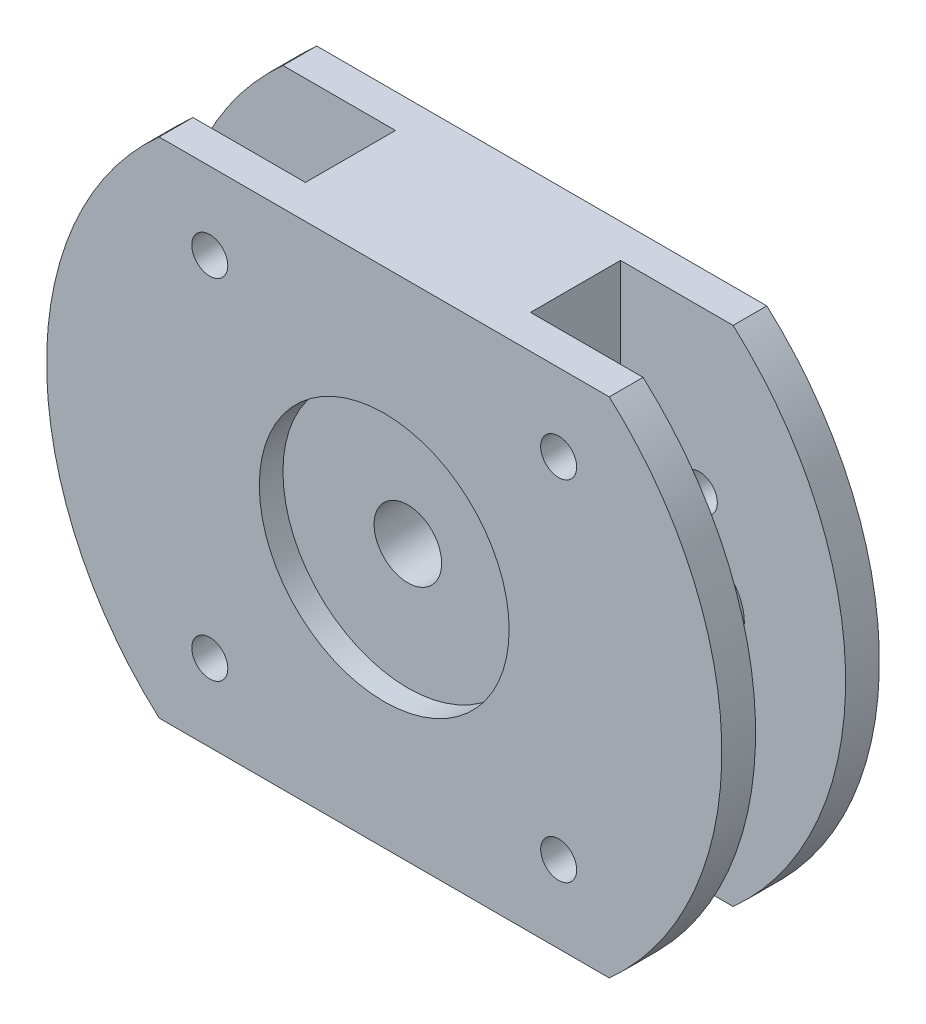
SolidWorks part; units mm, degrees
material "ABS"
ref_plane "前视基准面" through (0, 0, 0) normal (0, 0, 1) x (1, 0, 0)
ref_plane "上视基准面" through (0, 0, 0) normal (0, 1, 0) x (1, 0, 0)
ref_plane "右视基准面" through (0, 0, 0) normal (1, 0, 0) x (0, 0, -1)
sketch "草图1" plane through (0, 0, 0) normal (0, 0, 1) x (1, 0, 0)
  line L0 (-20, 22.3607) -> (20, 22.3607)
  line L1 (-20, -22.3607) -> (20, -22.3607)
  arc A0 (-20, 22.3607) -> (-20, -22.3607) centre (0, 0) ccw
  arc A1 (20, -22.3607) -> (20, 22.3607) centre (0, 0) ccw
  dimension "D1" = 60
  dimension "D2" = 40
  dimension "D3" = 40
extrude "凸台-拉伸1" add sketch "草图1" along normal blind 3
sketch "草图2" plane through (0, 0, 3) normal (0, 0, 1) x (1, 0, 0)
  line L0 (0, 0) -> (20, 0) construction
  line L1 (0, 0) -> (0, 24.5048) construction
  line L2 (17, 0) -> (17, 8) construction
  circle A0 centre (17, 8) radius 1.6
  circle A1 centre (-17, 0) radius 2.55
  circle A2 centre (17, 0) radius 2.55
  circle A3 centre (17, -8) radius 1.6
  circle A4 centre (-17, -8) radius 1.6
  circle A5 centre (-17, 8) radius 1.6
  dimension "D1" = 5.1
  dimension "D2" = 3.2
  dimension "D3" = 17
  dimension "D4" = 8
extrude "切除-拉伸1" cut sketch "草图2" against normal blind 5
sketch "草图3" plane through (0, 0, 3) normal (0, 0, 1) x (1, 0, 0)
  circle A0 centre (17, 0) radius 2.55 construction
  circle A1 centre (17, 0) radius 2.55
  circle A2 centre (-17, 0) radius 2.55 construction
  circle A3 centre (-17, 0) radius 2.55
  circle A4 centre (17, 0) radius 4
  circle A5 centre (-17, 0) radius 4
  dimension "D1" = 8
  dimension "D2" = 8
extrude "凸台-拉伸2" add sketch "草图3" along normal blind 8
sketch "草图4" plane through (0, 0, 11) normal (0, 0, 1) x (1, 0, 0)
  circle A0 centre (-17, 0) radius 4
  circle A1 centre (17, 0) radius 4
  dimension "D1" = 8
  dimension "D2" = 8
extrude "凸台-拉伸3" [suppressed] add sketch "草图4" against normal blind 5 contours A0 | A1
sketch "草图5" plane through (0, 0, 11) normal (0, 0, 1) x (1, 0, 0)
  line L0 (-20, -22.3607) -> (20, -22.3607) construction
  line L1 (20, 22.3607) -> (-20, 22.3607) construction
  line L2 (-20, -22.3607) -> (20, -22.3607)
  line L3 (20, 22.3607) -> (-20, 22.3607)
  arc A0 (20, -22.3607) -> (20, 22.3607) centre (0, 0) ccw construction
  arc A1 (-20, 22.3607) -> (-20, -22.3607) centre (0, 0) ccw construction
  arc A2 (20, -22.3607) -> (20, 22.3607) centre (0, 0) ccw
  arc A3 (-20, 22.3607) -> (-20, -22.3607) centre (0, 0) ccw
extrude "凸台-拉伸4" add sketch "草图5" along normal blind 3
sketch "草图6" plane through (0, 0, 3) normal (0, 0, 1) x (1, 0, 0)
  line L0 (20, 22.3607) -> (-20, 22.3607) construction
  line L1 (-10, 22.3607) -> (10, 22.3607)
  line L2 (-10, 22.3607) -> (-10, -22.3607)
  line L3 (-10, -22.3607) -> (10, -22.3607)
  line L4 (10, 22.3607) -> (10, -22.3607)
  line L5 (-20, -22.3607) -> (20, -22.3607) construction
  line L6 (0, 0) -> (0, 20) construction
  dimension "D1" = 20
extrude "凸台-拉伸5" add sketch "草图6" along normal up to next
sketch "草图8" plane through (0, 0, 14) normal (0, 0, 1) x (1, 0, 0)
  line L0 (0, 0) -> (33.7347, 0) construction
  line L1 (0, 0) -> (0, 30.9666) construction
  line L2 (15.5, 15.5) -> (0, 0) construction
  circle A0 centre (15.5, 15.5) radius 1.6
  circle A1 centre (15.5, -15.5) radius 1.6
  circle A2 centre (-15.5, -15.5) radius 1.6
  circle A3 centre (-15.5, 15.5) radius 1.6
  point P19 (0, 0)
  dimension "D1" = 3.2
  dimension "D2" = 45
  dimension "D3" = 15.5
  dimension "D4" = 4
extrude "切除-拉伸6" cut sketch "草图8" against normal blind 10
sketch "草图9" plane through (0, 0, 14) normal (0, 0, 1) x (1, 0, 0)
  circle A0 centre (0, 0) radius 3
  dimension "D1" = 6
extrude "切除-拉伸7" cut sketch "草图9" against normal blind 20
sketch "草图10" plane through (0, 0, 14) normal (0, 0, 1) x (1, 0, 0)
  circle A0 centre (0, 0) radius 11.1
  dimension "D1" = 22.2
extrude "切除-拉伸8" cut sketch "草图10" against normal blind 2.1
sketch "草图11" plane through (0, 0, 0) normal (0, 0, -1) x (-1, 0, 0)
  circle A0 centre (0, 0) radius 3
  circle A1 centre (0, 0) radius 5
  circle M2 centre (0, 0) radius 3
  dimension "D1" = 6
  dimension "D2" = 10
extrude "凸台-拉伸6" add sketch "草图11" along normal blind 2.4 contours A1 M2 | A0
fillet "圆角1" radius 0.5 3 edges at (-3, 0, -2.4) (5, 0, 0) (-5, 0, -2.4)
sketch "草图12" plane through (0, 0, 11) normal (0, 0, -1) x (-1, 0, 0)
  circle A0 centre (-17, 0) radius 2.55 construction
  circle A1 centre (17, 0) radius 2.55 construction
  circle A2 centre (-17, 0) radius 2.55
  circle A3 centre (17, 0) radius 2.55
extrude "凸台-拉伸7" add sketch "草图12" along normal blind 5
